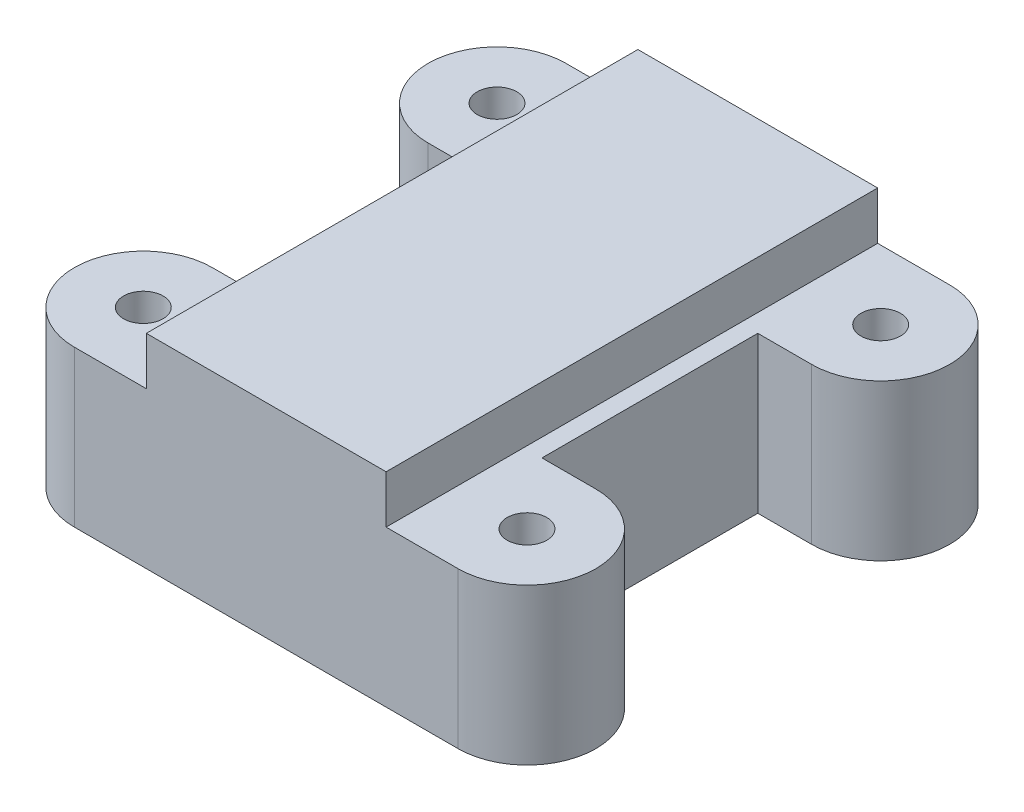
SolidWorks part; units mm, degrees
ref_plane "Front Plane" through (0, 0, 0) normal (0, 0, 1) x (1, 0, 0)
ref_plane "Top Plane" through (0, 0, 0) normal (0, 1, 0) x (1, 0, 0)
ref_plane "Right Plane" through (0, 0, 0) normal (1, 0, 0) x (0, 0, -1)
sketch "Sketch1" plane through (0, 0, 0) normal (0, 1, 0) x (1, 0, 0)
  line L0 (-16, 9) -> (-11.5, 9)
  line L1 (-16, 20.5) -> (16, 20.5)
  line L2 (0, 20.5) -> (0, 0)
  line L3 (0, 0) -> (-11.5, 0)
  line L4 (-21.75, 26.9491) -> (-21.75, 13.5796) construction
  line L5 (-11.5, 9) -> (-11.5, -9)
  line L6 (11.5, 9) -> (11.5, -9)
  line L7 (16, 9) -> (11.5, 9)
  line L8 (16, -9) -> (11.5, -9)
  line L9 (-16, -20.5) -> (16, -20.5)
  line L10 (-16, -9) -> (-11.5, -9)
  arc A0 (-16, 9) -> (-16, 20.5) centre (-16, 14.75) cw
  circle A1 centre (-16, 14.75) radius 1.65
  arc A2 (16, 9) -> (16, 20.5) centre (16, 14.75) ccw
  circle A3 centre (16, 14.75) radius 1.65
  circle A4 centre (16, -14.75) radius 1.65
  arc A5 (16, -9) -> (16, -20.5) centre (16, -14.75) cw
  circle A6 centre (-16, -14.75) radius 1.65
  arc A7 (-16, -9) -> (-16, -20.5) centre (-16, -14.75) ccw
  point P26 (11.5, 0)
  dimension "D2" = 5.75
  dimension "D5" = 3.3
  dimension "D1" = 11.5
  dimension "D3" = 21.75
  dimension "D4" = 20.5
extrude "Boss-Extrude1" add sketch "Sketch1" along normal blind 13 contours A7 L9 A5 L8 L6 L7 A2 L1 A0 L0 L5 L10 | A1 | A3 | A4 | A6
sketch "Sketch2" plane through (0, 13, 0) normal (0, 1, 0) x (1, 0, 0)
  line L0 (-16, 20.5) -> (16, 20.5) construction
  line L1 (-10, 20.5) -> (10, 20.5)
  line L2 (-10, 20.5) -> (-10, -20.5)
  line L3 (-10, -20.5) -> (10, -20.5)
  line L4 (10, 20.5) -> (10, -20.5)
  line L5 (-16, -20.5) -> (16, -20.5) construction
  line L6 (0, 31.1718) -> (0, -29.6701) construction
  dimension "D1" = 20
extrude "Boss-Extrude2" add sketch "Sketch2" along normal offset from surface (4 mm away) 17 up to face at (-16, 0, 13.1)
